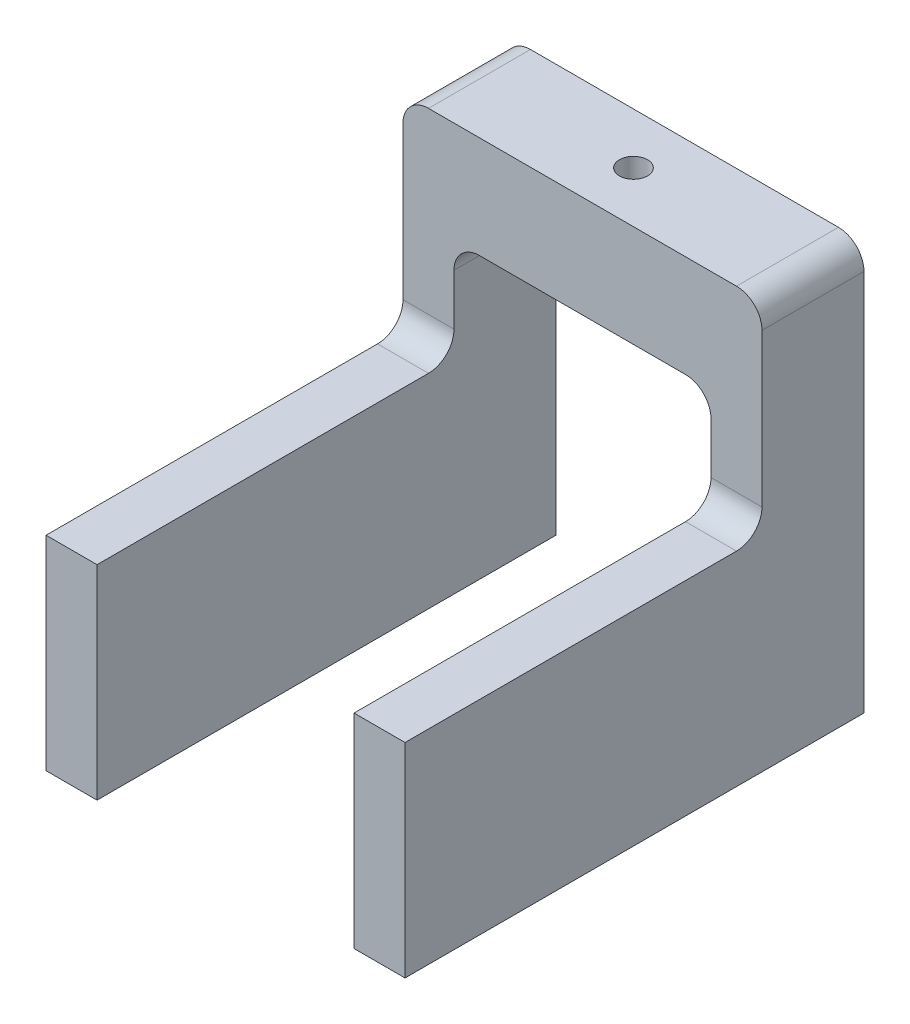
SolidWorks part; units mm, degrees
ref_plane "Front Plane" through (0, 0, 0) normal (0, 0, 1) x (1, 0, 0)
ref_plane "Top Plane" through (0, 0, 0) normal (0, 1, 0) x (1, 0, 0)
ref_plane "Right Plane" through (0, 0, 0) normal (1, 0, 0) x (0, 0, -1)
sketch "Sketch1" plane through (0, 0, 0) normal (1, 0, 0) x (0, 0, -1)
  line L0 (0, 0) -> (-114.3, 0)
  line L1 (-114.3, 0) -> (-114.3, 50.8)
  line L2 (-114.3, 50.8) -> (-25.4, 50.8)
  line L3 (-25.4, 50.8) -> (-25.4, 101.6)
  line L4 (-25.4, 101.6) -> (0, 101.6)
  line L5 (0, 101.6) -> (0, 0)
  point P7 (-12.7, 101.6)
  dimension "D1" = 101.6
  dimension "D2" = 50.8
  dimension "D3" = 101.6
  dimension "D4" = 25.4
extrude "Boss-Extrude1" add sketch "Sketch1" along normal blind 89.408
sketch "Sketch2" plane through (0, 0, 0) normal (0, 0, -1) x (-1, 0, 0)
  line L0 (-89.408, 0) -> (0, 0) construction
  line L1 (-76.708, 0) -> (-76.708, 76.2)
  line L2 (-76.708, 76.2) -> (-12.7, 76.2)
  line L3 (-12.7, 76.2) -> (-12.7, 0)
  line L4 (-12.7, 0) -> (-76.708, 0)
  line L5 (-89.408, 0) -> (-89.408, 101.6) construction
  line L6 (0, 0) -> (0, 101.6) construction
  line L7 (-89.408, 101.6) -> (0, 101.6) construction
  dimension "D1" = 12.7
  dimension "D2" = 12.7
  dimension "D3" = 25.4
extrude "Cut-Extrude1" cut sketch "Sketch2" against normal through all
hole_wizard "Ø7.0mm Dowel Hole1" positions "Sketch3" profile "Sketch4" hole size "Ø1.0" standard "ANSI Metric" end condition through all
sketch "Sketch3" plane through (0, 101.6, 0) normal (0, 1, 0) x (1, 0, 0)
  point P0 (44.704, -12.7)
  dimension "D1" = 44.704
  dimension "D2" = 12.7
sketch "Sketch4" plane through (44.704, 101.6, 12.7) normal (1, 0, 0) x (0, 0, 1)
  line L0 (0, 0) -> (0, 101.6)
  line L1 (0, 101.6) -> (3.5, 101.6)
  line L2 (3.5, 101.6) -> (3.5, 0)
  line L5 (3.5, 0) -> (0, 0)
  line L11 (0, -6.35) -> (0, 107.95) construction
  dimension "Thru Hole Dia." = 7
  dimension "Thru Hole Depth" = 101.6
fillet "Fillet1" radius 6.35 6 edges at (76.708, 76.2, 12.7) (12.7, 76.2, 12.7) (6.35, 50.8, 25.4) (83.058, 50.8, 25.4) (89.408, 101.6, 12.7) (0, 101.6, 12.7)
